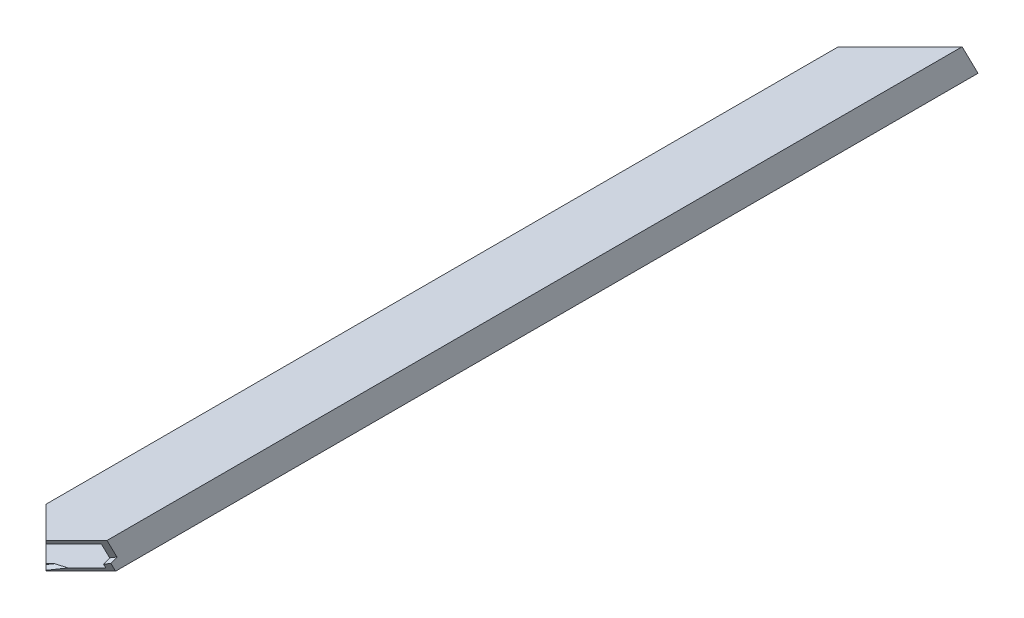
SolidWorks part; units mm, degrees
ref_plane "Front Plane" through (0, 0, 0) normal (0, 0, 1) x (1, 0, 0)
ref_plane "Top Plane" through (0, 0, 0) normal (0, 1, 0) x (1, 0, 0)
ref_plane "Right Plane" through (0, 0, 0) normal (1, 0, 0) x (0, 0, -1)
sketch "Sketch1" plane through (0, 0, 0) normal (0, 0, 1) x (1, 0, 0)
  line L0 (-22.225, 9.525) -> (22.225, 9.525)
  line L1 (-25.4, -12.7) -> (25.4, -12.7)
  line L2 (-25.4, -12.7) -> (-25.4, 12.7)
  line L3 (-25.4, 12.7) -> (25.4, 12.7)
  line L4 (25.4, -12.7) -> (25.4, 12.7)
  line L5 (-25.4, -12.7) -> (25.4, 12.7) construction
  line L6 (-25.4, 12.7) -> (25.4, -12.7) construction
  line L7 (22.225, -9.525) -> (22.225, 9.525)
  line L8 (-22.225, -9.525) -> (22.225, -9.525)
  line L9 (-22.225, -9.525) -> (-22.225, 9.525)
  point P0 (0, 0)
  dimension "D1" = 25.4
  dimension "D2" = 50.8
  dimension "D3" = 3.175
extrude "Boss-Extrude1" add sketch "Sketch1" along normal blind 771.9314
sketch "Sketch2" plane through (0, 12.7, 0) normal (0, 1, 0) x (1, 0, 0)
  line L0 (25.4, 0) -> (-25.4, -50.8)
  line L1 (-25.4, -771.9314) -> (-25.4, 0) construction
  line L2 (-25.4, -50.8) -> (-25.4, 0)
  line L3 (-25.4, 0) -> (25.4, 0)
  line L4 (-25.4, -771.9314) -> (25.4, -721.1314)
  line L5 (25.4, -771.9314) -> (25.4, 0) construction
  line L6 (25.4, -721.1314) -> (25.4, -771.9314)
  line L7 (25.4, -771.9314) -> (-25.4, -771.9314)
  dimension "D1" = 45
  dimension "D2" = 45
extrude "Cut-Extrude1" cut sketch "Sketch2" against normal through all
ref_plane "Plane1" through (12.7, 0, -12.7) normal (-0.7071, 0, 0.7071) x (0, 1, 0)
sketch "Sketch5" plane through (12.7, 0, -12.7) normal (-0.7071, 0, 0.7071) x (0, 1, 0)
  line L0 (12.7, -17.9605) -> (12.7, -27.2054)
  line L1 (12.7, -527.8774) -> (12.7, -17.9605) construction
  line L2 (12.7, -27.2054) -> (-12.7, -17.9605)
  line L3 (-12.7, -17.9605) -> (12.7, -17.9605)
  line L4 (12.7, -527.8774) -> (-12.7, -518.6326)
  line L5 (-12.7, -527.8774) -> (-12.7, -17.9605) construction
  line L6 (-12.7, -518.6326) -> (-12.7, -527.8774)
  line L7 (-12.7, -527.8774) -> (12.7, -527.8774)
  dimension "D1" = 20
  dimension "D2" = 20
extrude "Cut-Extrude4" cut sketch "Sketch5" along normal blind 754.3292
sketch "Sketch7" plane through (326.7157, -168.1709, 326.7157) normal (0.6645, -0.342, 0.6645) x (0.5736, -0.3364, -0.7468)
  line L0 (-595.3376, -22.1334) -> (-492.8684, 40.7061)
  line L1 (-595.3376, -22.1334) -> (-578.0634, -50.3016)
  line L2 (-492.8684, 40.7061) -> (-475.5942, 12.5378)
  line L3 (-578.0634, -50.3016) -> (-475.5942, 12.5378)
extrude "Cut-Extrude5" cut sketch "Sketch7" against normal blind 4.0132
sketch "Sketch9" plane through (0, 0, 0) normal (0, 1, 0) x (1, 0, 0)
  line L0 (25.4, -715.0916) -> (25.4, -13.0742) construction
  line L1 (-25.4, -765.8916) -> (25.4, -765.8916)
  line L2 (-25.4, -765.8916) -> (-25.4, -744.8604)
  line L3 (-25.4, -744.8604) -> (25.4, -744.8604)
  line L4 (25.4, -765.8916) -> (25.4, -744.8604)
  point P7 (0, -744.8604)
  dimension "D1" = 21.0312
extrude "Cut-Extrude7" cut sketch "Sketch9" against normal mid plane 33.7312
ref_plane "Plane5" through (-369.8785, 0, 369.8785) normal (0.7071, 0, -0.7071) x (-0.7071, 0, -0.7071)
sketch "Sketch10" plane through (-369.8785, 0, 369.8785) normal (0.7071, 0, -0.7071) x (-0.7071, 0, -0.7071)
  line L1 (-526.9974, -41.2775) -> (-449.2638, -41.2775)
  line L2 (-526.9974, -41.2775) -> (-526.9974, 88.6294)
  line L3 (-526.9974, 88.6294) -> (-449.2638, 88.6294)
  line L4 (-449.2638, -41.2775) -> (-449.2638, 88.6294)
extrude "Cut-Extrude8" cut sketch "Sketch10" against normal blind 40.64
